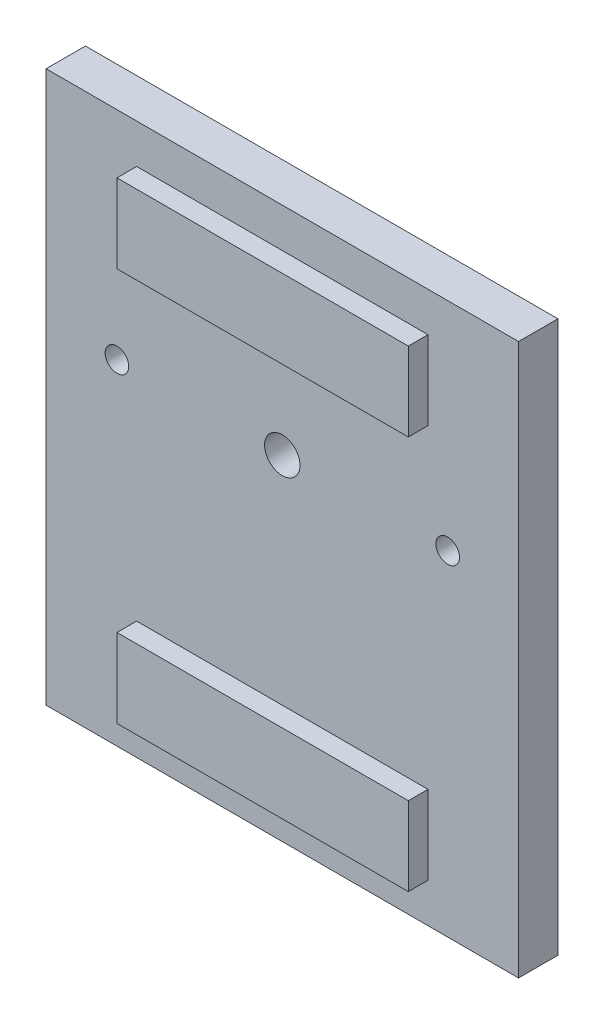
SolidWorks part; units mm, degrees
ref_plane "Front Plane" through (0, 0, 0) normal (0, 0, 1) x (1, 0, 0)
ref_plane "Top Plane" through (0, 0, 0) normal (0, 1, 0) x (1, 0, 0)
ref_plane "Right Plane" through (0, 0, 0) normal (1, 0, 0) x (0, 0, -1)
sketch "Sketch1" plane through (0, 0, 0) normal (0, 0, 1) x (1, 0, 0)
  line L1 (0, 0) -> (-120, 0)
  line L2 (0, 0) -> (0, -140)
  line L3 (0, -140) -> (-120, -140)
  line L4 (-120, 0) -> (-120, -140)
  point P5 (0, 0)
  dimension "D1" = 120
  dimension "D2" = 140
extrude "Boss-Extrude1" add sketch "Sketch1" along normal blind 10
sketch "Sketch2" plane through (0, 0, 10) normal (0, 0, 1) x (1, 0, 0)
  line L1 (-97, -10) -> (-23, -10)
  line L2 (-97, -10) -> (-97, -30)
  line L3 (-97, -30) -> (-23, -30)
  line L4 (-23, -10) -> (-23, -30)
  line L7 (0, 0) -> (-120, 0) construction
  line L8 (-120, 0) -> (-120, -140) construction
  line L9 (0, -140) -> (0, 0) construction
  line L10 (-120, -140) -> (0, -140) construction
  line L12 (-97, -110) -> (-23, -110)
  line L13 (-97, -110) -> (-97, -130)
  line L14 (-97, -130) -> (-23, -130)
  line L15 (-23, -110) -> (-23, -130)
  dimension "D1" = 23
  dimension "D2" = 23
  dimension "D3" = 110
  dimension "D4" = 10
  dimension "D5" = 23
  dimension "D6" = 23
  dimension "D7" = 10
  dimension "D8" = 110
extrude "Boss-Extrude2" add sketch "Sketch2" along normal blind 5
sketch "Sketch4" plane through (0, 0, 15) normal (0, 0, 1) x (1, 0, 0)
  line L0 (0, 0) -> (-120, 0) construction
  line L1 (0, 0) -> (-120, 0) construction
  line L2 (-120, 0) -> (-120, -140) construction
  circle A0 centre (-102, -55) radius 3
  circle A1 centre (-60, -55) radius 4.5
  circle A2 centre (-18, -55) radius 3
  dimension "D1" = 6
  dimension "D2" = 9
  dimension "D3" = 6
  dimension "D4" = 55
  dimension "D5" = 55
  dimension "D6" = 55
  dimension "D7" = 18
  dimension "D8" = 60
  dimension "D9" = 102
extrude "Cut-Extrude1" cut sketch "Sketch4" against normal blind 15
